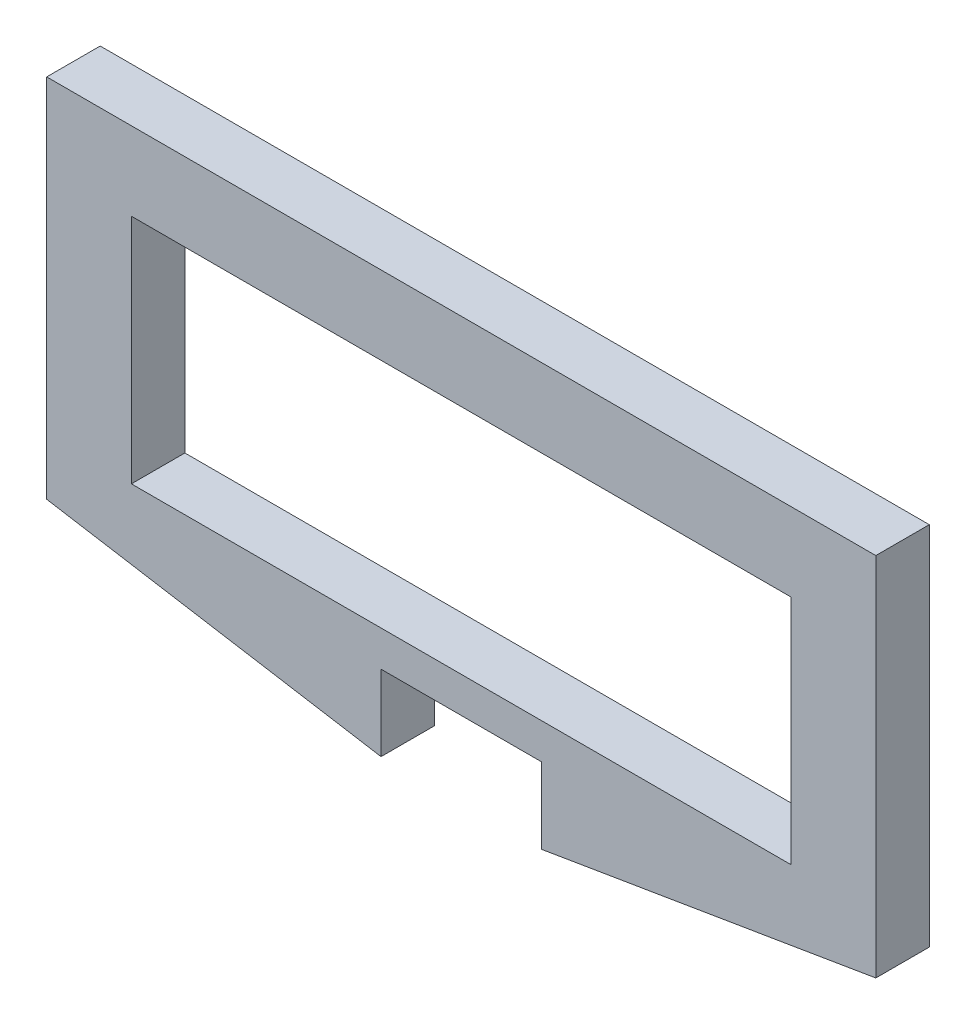
SolidWorks part; units mm, degrees
ref_plane "Ön Düzlem" through (0, 0, 0) normal (0, 0, 1) x (1, 0, 0)
ref_plane "Üst Düzlem" through (0, 0, 0) normal (0, 1, 0) x (1, 0, 0)
ref_plane "Sağ Düzlem" through (0, 0, 0) normal (1, 0, 0) x (0, 0, -1)
sketch "Çizim1" plane through (0, 0, 0) normal (0, 0, 1) x (1, 0, 0)
  line L0 (0, -125.1949) -> (0, 89.4537) construction
  line L1 (-34.1906, 0) -> (32.789, 0) construction
  line L2 (232.49, 9.8912) -> (-232.49, 9.8912)
  line L3 (-232.49, 9.8912) -> (-232.49, -195.2888)
  line L4 (-232.49, -195.2888) -> (-45, -226.5293)
  line L5 (-45, -226.5293) -> (-45, -184.0293)
  line L6 (-45, -184.0293) -> (45, -184.0293)
  line L7 (0, -184.0293) -> (0, -164.0293) construction
  line L8 (185, -164.0293) -> (-185, -164.0293)
  line L9 (-185, -164.0293) -> (-185, -34.0293)
  line L10 (-185, -34.0293) -> (185, -34.0293)
  line L11 (45, -226.5293) -> (45, -184.0293)
  line L12 (185, -164.0293) -> (185, -34.0293)
  line L13 (232.49, -195.2888) -> (45, -226.5293)
  line L14 (232.49, 9.8912) -> (232.49, -195.2888)
  point P14 (0, 9.8912)
  point P21 (0, -34.0293)
  dimension "D1" = 45
  dimension "D2" = 42.5
  dimension "D3" = 80.54
  dimension "D4" = 232.49
  dimension "D5" = 190.0749
  dimension "D6" = 205.18
extrude "Yükseklik-Ekstrüzyon1" add sketch "Çizim1" along normal blind 30
